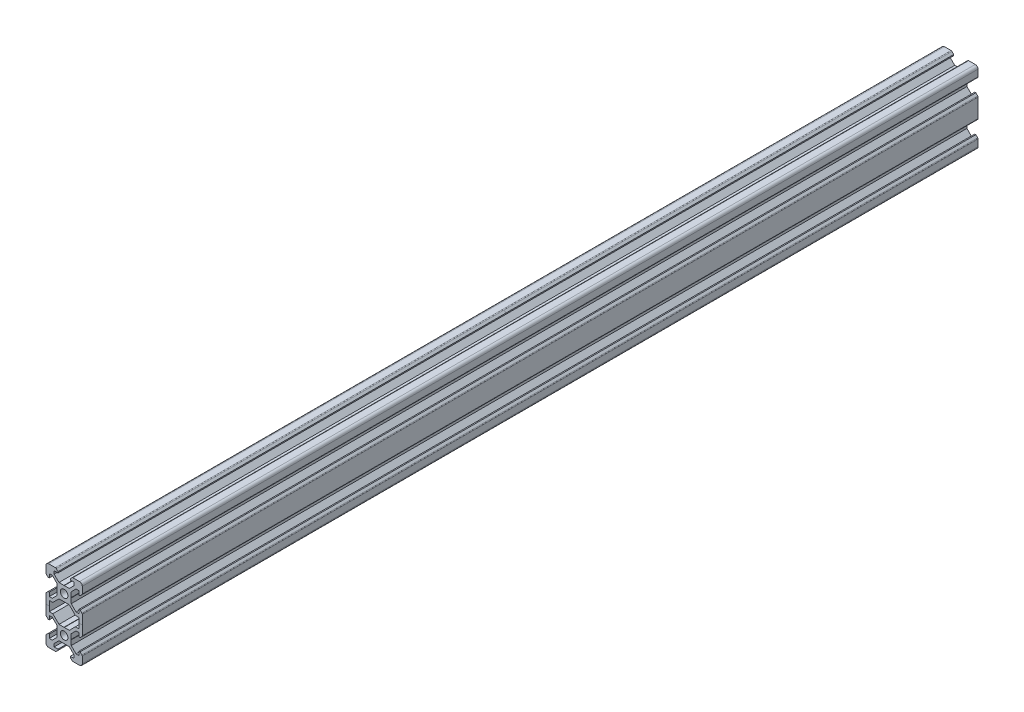
SolidWorks part; units mm, degrees
material "6063-T5"
ref_plane "Front" through (0, 0, 0) normal (0, 0, 1) x (1, 0, 0)
ref_plane "Top" through (0, 0, 0) normal (0, 1, 0) x (1, 0, 0)
ref_plane "Right" through (0, 0, 0) normal (1, 0, 0) x (0, 0, -1)
sketch "Sketch1" plane through (0, 0, 0) normal (0, 0, 1) x (1, 0, 0)
  line L0 (-8.5, 10) -> (-10, 8.5) construction
  line L1 (-8.5, 10) -> (-4.8628, 10)
  line L2 (-10, 8.5) -> (-10, 4.8628)
  line L4 (10, 8.5) -> (10, 4.8628)
  line L5 (-10, 10) -> (10, -10) construction
  line L6 (-10, -10) -> (10, 10) construction
  line L7 (8.2, -5.5) -> (8.2, -3.3865)
  line L8 (-8.2, -5.5) -> (-8.2, -3.3865)
  line L9 (-5.5, 8.2) -> (-3.3865, 8.2)
  line L10 (-8.2, -12.7) -> (-8.2, -7.3)
  line L11 (-3.9005, 2.8395) -> (-6.561, 5.5)
  line L12 (-6.561, 5.5) -> (-8.2, 5.5)
  line L13 (-2.8395, -3.9005) -> (-0.1, -3.9005)
  line L14 (-3.9005, -2.8395) -> (-3.9005, -0.1)
  line L15 (-2.8395, 3.9005) -> (-0.1, 3.9005)
  line L16 (3.9005, -2.8395) -> (3.9005, -0.1)
  line L17 (-8.2, 3.3865) -> (-8.81, 3.3865)
  line L18 (-8.81, 3.3865) -> (-9.7976, 4.3741)
  line L19 (8.5, 10) -> (10, 8.5) construction
  line L20 (-2.8395, 3.9005) -> (-5.5, 6.561)
  line L21 (-5.5, 6.561) -> (-5.5, 8.2)
  line L22 (-3.3865, 8.2) -> (-3.3865, 8.81)
  line L23 (-3.3865, 8.81) -> (-4.3741, 9.7976)
  line L24 (0, 24.069) -> (0, -33.8154) construction
  line L25 (3.3865, 8.81) -> (4.3741, 9.7976)
  line L26 (3.3865, 8.2) -> (3.3865, 8.81)
  line L27 (5.5, 6.561) -> (5.5, 8.2)
  line L28 (2.8395, 3.9005) -> (5.5, 6.561)
  line L29 (3.3865, 8.2) -> (5.5, 8.2)
  line L30 (4.8628, 10) -> (8.5, 10)
  line L31 (-0.1, 3.9005) -> (0, 3.8005)
  line L32 (0.1, 3.9005) -> (0, 3.8005)
  line L33 (0.1, 3.9005) -> (2.8395, 3.9005)
  line L34 (25.9287, 0) -> (-28.3459, 0) construction
  line L35 (-0.1, -3.9005) -> (0, -3.8005)
  line L36 (0.1, -3.9005) -> (0, -3.8005)
  line L37 (0.1, -3.9005) -> (2.8395, -3.9005)
  line L38 (-3.9005, 0.1) -> (-3.8005, 0)
  line L39 (-3.8005, 0) -> (-3.9005, -0.1)
  line L40 (-3.9005, 0.1) -> (-3.9005, 2.8395)
  line L41 (3.9005, 0.1) -> (3.8005, 0)
  line L42 (3.8005, 0) -> (3.9005, -0.1)
  line L43 (3.9005, 0.1) -> (3.9005, 2.8395)
  line L44 (8.81, 3.3865) -> (9.7976, 4.3741)
  line L45 (8.2, 3.3865) -> (8.81, 3.3865)
  line L46 (6.561, 5.5) -> (8.2, 5.5)
  line L47 (3.9005, 2.8395) -> (6.561, 5.5)
  line L48 (2.8395, -3.9005) -> (5.5, -6.561)
  line L49 (3.9005, -2.8395) -> (6.561, -5.5)
  line L50 (-2.8395, -3.9005) -> (-5.5, -6.561)
  line L51 (-3.9005, -2.8395) -> (-6.561, -5.5)
  line L52 (6.561, -5.5) -> (8.2, -5.5)
  line L53 (-6.561, -5.5) -> (-8.2, -5.5)
  line L54 (-8.81, -3.3865) -> (-9.7976, -4.3741)
  line L55 (-8.2, -3.3865) -> (-8.81, -3.3865)
  line L56 (8.81, -3.3865) -> (9.7976, -4.3741)
  line L57 (8.2, -3.3865) -> (8.81, -3.3865)
  line L58 (8.2, 3.3865) -> (8.2, 5.5)
  line L59 (10, -4.8628) -> (10, -15.1372)
  line L60 (-8.2, 3.3865) -> (-8.2, 5.5)
  line L61 (-10, -4.8628) -> (-10, -15.1372)
  line L62 (-28.3459, -10) -> (-10, -10) construction
  line L63 (-3.9005, -20.1) -> (-3.9005, -22.8395)
  line L64 (-3.9005, -20.1) -> (-3.8005, -20)
  line L65 (-3.8005, -20) -> (-3.9005, -19.9)
  line L66 (3.9005, -20.1) -> (3.9005, -22.8395)
  line L67 (3.9005, -20.1) -> (3.8005, -20)
  line L68 (3.8005, -20) -> (3.9005, -19.9)
  line L69 (6.561, -14.5) -> (8.2, -14.5)
  line L70 (3.9005, -17.1605) -> (6.561, -14.5)
  line L71 (3.9005, -17.1605) -> (3.9005, -19.9)
  line L72 (-3.9005, -17.1605) -> (-3.9005, -19.9)
  line L73 (-3.9005, -17.1605) -> (-6.561, -14.5)
  line L74 (-6.561, -14.5) -> (-8.2, -14.5)
  line L75 (-8.2, -16.6135) -> (-8.81, -16.6135)
  line L76 (-8.81, -16.6135) -> (-9.7976, -15.6259)
  line L77 (8.2, -16.6135) -> (8.81, -16.6135)
  line L78 (8.81, -16.6135) -> (9.7976, -15.6259)
  line L79 (-2.8395, -16.0995) -> (-5.5, -13.439)
  line L80 (-2.8395, -16.0995) -> (-0.1, -16.0995)
  line L81 (-0.1, -16.0995) -> (0, -16.1995)
  line L82 (0.1, -16.0995) -> (0, -16.1995)
  line L83 (0.1, -16.0995) -> (2.8395, -16.0995)
  line L84 (2.8395, -16.0995) -> (5.5, -13.439)
  line L85 (-8.2, -16.6135) -> (-8.2, -14.5)
  line L86 (8.2, -16.6135) -> (8.2, -14.5)
  line L87 (2.8395, -23.9005) -> (5.5, -26.561)
  line L88 (-2.8395, -23.9005) -> (-5.5, -26.561)
  line L89 (-0.1, -23.9005) -> (0, -23.8005)
  line L90 (0.1, -23.9005) -> (0, -23.8005)
  line L91 (0.1, -23.9005) -> (2.8395, -23.9005)
  line L92 (-2.8395, -23.9005) -> (-0.1, -23.9005)
  line L93 (-10, -28.5) -> (-10, -24.8628)
  line L94 (10, -28.5) -> (10, -24.8628)
  line L95 (8.81, -23.3865) -> (9.7976, -24.3741)
  line L96 (-8.81, -23.3865) -> (-9.7976, -24.3741)
  line L97 (-8.2, -23.3865) -> (-8.81, -23.3865)
  line L98 (8.2, -23.3865) -> (8.81, -23.3865)
  line L99 (8.2, -23.3865) -> (8.2, -25.5)
  line L100 (-8.2, -23.3865) -> (-8.2, -25.5)
  line L101 (-6.561, -25.5) -> (-8.2, -25.5)
  line L102 (6.561, -25.5) -> (8.2, -25.5)
  line L103 (3.9005, -22.8395) -> (6.561, -25.5)
  line L104 (-3.9005, -22.8395) -> (-6.561, -25.5)
  line L105 (-5.5, -28.2) -> (-3.3865, -28.2)
  line L106 (3.3865, -28.2) -> (5.5, -28.2)
  line L107 (3.3865, -28.2) -> (3.3865, -28.81)
  line L108 (3.3865, -28.81) -> (4.3741, -29.7976)
  line L109 (-3.3865, -28.2) -> (-3.3865, -28.81)
  line L110 (-3.3865, -28.81) -> (-4.3741, -29.7976)
  line L111 (-8.5, -30) -> (-4.8628, -30)
  line L112 (4.8628, -30) -> (8.5, -30)
  line L113 (-5.5, -26.561) -> (-5.5, -28.2)
  line L114 (5.5, -26.561) -> (5.5, -28.2)
  line L115 (-6.239, -7.3) -> (-8.2, -7.3)
  line L116 (-5.5, -6.561) -> (-6.239, -7.3)
  line L117 (6.239, -7.3) -> (8.2, -7.3)
  line L118 (5.5, -6.561) -> (6.239, -7.3)
  line L119 (-6.239, -12.7) -> (-8.2, -12.7)
  line L120 (-5.5, -13.439) -> (-6.239, -12.7)
  line L121 (5.5, -13.439) -> (6.239, -12.7)
  line L122 (6.239, -12.7) -> (8.2, -12.7)
  line L123 (8.2, -12.7) -> (8.2, -7.3)
  line L125 (10, -10) -> (25.9287, -10) construction
  circle A0 centre (0, 0) radius 2.1
  arc A1 (-8.5, 10) -> (-10, 8.5) centre (-8.5, 8.5) ccw
  arc A2 (10, 8.5) -> (8.5, 10) centre (8.5, 8.5) ccw
  arc A3 (-4.3741, 9.7976) -> (-4.8628, 10) centre (-4.8628, 9.3088) ccw
  arc A4 (4.8628, 10) -> (4.3741, 9.7976) centre (4.8628, 9.3088) ccw
  circle A5 centre (0, -20) radius 2.1
  arc A6 (9.7976, 4.3741) -> (10, 4.8628) centre (9.3088, 4.8628) ccw
  arc A7 (-10, 4.8628) -> (-9.7976, 4.3741) centre (-9.3088, 4.8628) ccw
  arc A8 (-10, -4.8628) -> (-9.7976, -4.3741) centre (-9.3088, -4.8628) cw
  arc A9 (9.7976, -4.3741) -> (10, -4.8628) centre (9.3088, -4.8628) cw
  arc A10 (-10, -15.1372) -> (-9.7976, -15.6259) centre (-9.3088, -15.1372) ccw
  arc A11 (9.7976, -15.6259) -> (10, -15.1372) centre (9.3088, -15.1372) ccw
  arc A12 (-10, -24.8628) -> (-9.7976, -24.3741) centre (-9.3088, -24.8628) cw
  arc A13 (9.7976, -24.3741) -> (10, -24.8628) centre (9.3088, -24.8628) cw
  arc A14 (4.8628, -30) -> (4.3741, -29.7976) centre (4.8628, -29.3088) cw
  arc A15 (-4.3741, -29.7976) -> (-4.8628, -30) centre (-4.8628, -29.3088) cw
  arc A16 (-8.5, -30) -> (-10, -28.5) centre (-8.5, -28.5) cw
  arc A17 (10, -28.5) -> (8.5, -30) centre (8.5, -28.5) cw
  point P17 (-9.25, 9.25)
  point P21 (9.25, 9.25)
  dimension "D2" = 4.2
  dimension "D4" = 1.5
  dimension "D3" = 20
  dimension "D5" = 0.529
  dimension "D6" = 6.773
  dimension "D7" = 90
  dimension "D8" = 11
  dimension "D9" = 0.61
  dimension "D10" = 0.1
  dimension "D11" = 0.1
  dimension "D12" = 0.1
  dimension "D13" = 0.1
  dimension "D14" = 5.679
  dimension "D15" = 1.639
  dimension "D16" = 1.8
  dimension "D17" = 90
  dimension "D18" = 6.773
  dimension "D19" = 90
  dimension "D20" = 20
  dimension "D21" = 1.8
extrude "Boss-Extrude2" add sketch "Sketch1" along normal blind 494
sketch "Sketch2" plane through (0, 0, 0) normal (0, 0, -1) x (-1, 0, 0)
  line L0 (-10, -10) -> (10, -10)
  line L1 (-10, -15.1372) -> (-10, -4.8628) construction
  line L2 (10, -4.8628) -> (10, -15.1372) construction
split line "SideFixture1 - SplitLine"
sketch "Sketch3" plane through (0, 0, 494) normal (0, 0, 1) x (1, 0, 0)
  line L0 (-10, -10) -> (10, -10)
  line L1 (-10, -4.8628) -> (-10, -15.1372) construction
  line L2 (10, -15.1372) -> (10, -4.8628) construction
split line "SideFixture2 - SplitLine"
sketch "Sketch4" plane through (0, 10, 0) normal (0, 1, 0) x (1, 0, 0)
  line L0 (-8.5, -247) -> (8.5, -247)
  line L1 (-8.5, -494) -> (-8.5, 0) construction
  line L2 (8.5, -494) -> (8.5, 0) construction
split line "SideFixture3 - SplitLine"
